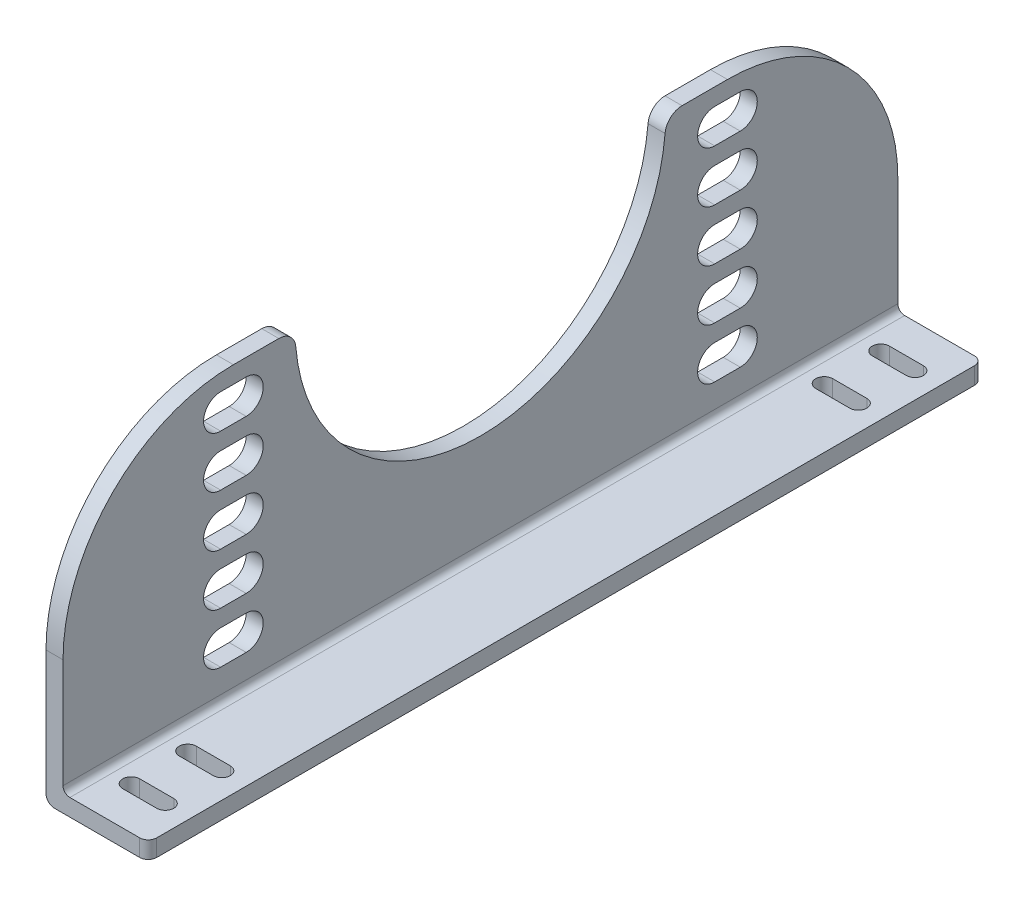
SolidWorks part; units mm, degrees
material "PA9"
ref_plane "Płaszczyzna przednia" through (0, 0, 0) normal (0, 0, 1) x (1, 0, 0)
ref_plane "Płaszczyzna górna" through (0, 0, 0) normal (0, 1, 0) x (1, 0, 0)
ref_plane "Płaszczyzna prawa" through (0, 0, 0) normal (1, 0, 0) x (0, 0, -1)
sketch "Szkic1" plane through (0, 0, 0) normal (0, 0, 1) x (1, 0, 0)
  line L1 (0, 0) -> (-10, 0)
  line L2 (0, 0) -> (0, 178)
  line L3 (0, 178) -> (-10, 178)
  line L4 (-10, 0) -> (-10, 178)
  dimension "D1" = 10
  dimension "D2" = 178
extrude "Dodanie-wyciągnięcie1" add sketch "Szkic1" along normal blind 490
sketch "Szkic2" plane through (0, 0, 0) normal (1, 0, 0) x (0, 0, -1)
  line L0 (-107.5, 158) -> (-92.5, 158) construction
  line L1 (-107.5, 168) -> (-92.5, 168)
  line L2 (-107.5, 148) -> (-92.5, 148)
  line L3 (-490, 178) -> (0, 178) construction
  line L5 (-107.5, 128) -> (-92.5, 128) construction
  line L6 (-107.5, 138) -> (-92.5, 138)
  line L7 (-107.5, 118) -> (-92.5, 118)
  line L8 (-107.5, 98) -> (-92.5, 98) construction
  line L9 (-107.5, 108) -> (-92.5, 108)
  line L10 (-107.5, 88) -> (-92.5, 88)
  line L11 (-107.5, 68) -> (-92.5, 68) construction
  line L12 (-107.5, 78) -> (-92.5, 78)
  line L13 (-107.5, 58) -> (-92.5, 58)
  line L14 (-107.5, 38) -> (-92.5, 38) construction
  line L15 (-107.5, 48) -> (-92.5, 48)
  line L16 (-107.5, 28) -> (-92.5, 28)
  line L17 (0, 0) -> (0, 178) construction
  arc A0 (-107.5, 168) -> (-107.5, 148) centre (-107.5, 158) ccw
  arc A1 (-92.5, 148) -> (-92.5, 168) centre (-92.5, 158) ccw
  arc A2 (-107.5, 138) -> (-107.5, 118) centre (-107.5, 128) ccw
  arc A3 (-92.5, 118) -> (-92.5, 138) centre (-92.5, 128) ccw
  arc A4 (-107.5, 108) -> (-107.5, 88) centre (-107.5, 98) ccw
  arc A5 (-92.5, 88) -> (-92.5, 108) centre (-92.5, 98) ccw
  arc A6 (-107.5, 78) -> (-107.5, 58) centre (-107.5, 68) ccw
  arc A7 (-92.5, 58) -> (-92.5, 78) centre (-92.5, 68) ccw
  arc A8 (-107.5, 48) -> (-107.5, 28) centre (-107.5, 38) ccw
  arc A9 (-92.5, 28) -> (-92.5, 48) centre (-92.5, 38) ccw
  point P2 (-100, 158)
  point P15 (-100, 128)
  point P22 (-100, 98)
  point P29 (-100, 68)
  point P36 (-100, 38)
  dimension "D1" = 10
  dimension "D2" = 15
  dimension "D3" = 20
  dimension "D4" = 100
  dimension "D5" = 5
extrude "Wytnij-wyciągnięcie1" cut sketch "Szkic2" against normal through all
sketch "Szkic3" plane through (0, 0, 0) normal (1, 0, 0) x (0, 0, -1)
  line L0 (-397.5, 158) -> (-382.5, 158) construction
  line L1 (-397.5, 168) -> (-382.5, 168)
  line L2 (-397.5, 148) -> (-382.5, 148)
  line L3 (-490, 178) -> (0, 178) construction
  line L4 (-92.5, 168) -> (-107.5, 168) construction
  line L5 (-397.5, 128) -> (-382.5, 128) construction
  line L6 (-397.5, 138) -> (-382.5, 138)
  line L7 (-397.5, 118) -> (-382.5, 118)
  line L8 (-397.5, 98) -> (-382.5, 98) construction
  line L9 (-397.5, 108) -> (-382.5, 108)
  line L10 (-397.5, 88) -> (-382.5, 88)
  line L11 (-397.5, 68) -> (-382.5, 68) construction
  line L12 (-397.5, 78) -> (-382.5, 78)
  line L13 (-397.5, 58) -> (-382.5, 58)
  line L14 (-397.5, 38) -> (-382.5, 38) construction
  line L15 (-397.5, 48) -> (-382.5, 48)
  line L16 (-397.5, 28) -> (-382.5, 28)
  arc A0 (-397.5, 168) -> (-397.5, 148) centre (-397.5, 158) ccw
  arc A1 (-382.5, 148) -> (-382.5, 168) centre (-382.5, 158) ccw
  arc A2 (-397.5, 138) -> (-397.5, 118) centre (-397.5, 128) ccw
  arc A3 (-382.5, 118) -> (-382.5, 138) centre (-382.5, 128) ccw
  arc A4 (-397.5, 108) -> (-397.5, 88) centre (-397.5, 98) ccw
  arc A5 (-382.5, 88) -> (-382.5, 108) centre (-382.5, 98) ccw
  arc A6 (-397.5, 78) -> (-397.5, 58) centre (-397.5, 68) ccw
  arc A7 (-382.5, 58) -> (-382.5, 78) centre (-382.5, 68) ccw
  arc A8 (-397.5, 48) -> (-397.5, 28) centre (-397.5, 38) ccw
  arc A9 (-382.5, 28) -> (-382.5, 48) centre (-382.5, 38) ccw
  point P2 (-390, 158)
  point P11 (-100, 168)
  point P15 (-390, 128)
  point P22 (-390, 98)
  point P29 (-390, 68)
  point P36 (-390, 38)
  dimension "D1" = 10
  dimension "D2" = 15
  dimension "D3" = 20
  dimension "D4" = 290
  dimension "D5" = 5
extrude "Wytnij-wyciągnięcie2" cut sketch "Szkic3" against normal through all
fillet "Zaokrąglenie1" radius 100 1 edges at (-5, 178, 0)
fillet "Zaokrąglenie2" radius 100 1 edges at (-5, 178, 490)
sketch "Szkic5" plane through (-10, 0, 0) normal (-1, 0, 0) x (0, 0, 1)
  line L0 (390, 178) -> (100, 178) construction
  line L1 (136.2352, 178) -> (353.7648, 178)
  arc A0 (136.2352, 178) -> (353.7648, 178) centre (245, 178) ccw
extrude "Wytnij-wyciągnięcie3" cut sketch "Szkic5" against normal through all
fillet "Zaokrąglenie3" radius 10 2 edges at (-5, 178, 353.7648) (-5, 178, 136.2352)
sketch "Szkic6" plane through (0, 0, 0) normal (0, 0, -1) x (-1, 0, 0)
  line L1 (10, 0) -> (-50, 0)
  line L2 (10, 0) -> (10, 10)
  line L3 (10, 10) -> (-50, 10)
  line L4 (-50, 0) -> (-50, 10)
  dimension "D1" = 60
  dimension "D2" = 10
extrude "Dodanie-wyciągnięcie2" add sketch "Szkic6" against normal through all
fillet "Zaokrąglenie4" radius 5 1 edges at (-10, 0, 245)
fillet "Zaokrąglenie5" radius 4 1 edges at (0, 10, 245)
fillet "Zaokrąglenie6" radius 5 2 edges at (50, 5, 0) (50, 5, 490)
sketch "Szkic7" plane through (0, 10, 0) normal (0, 1, 0) x (1, 0, 0)
  line L0 (35, -465) -> (15, -465) construction
  line L1 (35, -470) -> (15, -470)
  line L2 (35, -460) -> (15, -460)
  line L3 (4, -490) -> (45, -490) construction
  line L4 (50, -485) -> (50, -5) construction
  arc A0 (35, -470) -> (35, -460) centre (35, -465) ccw
  arc A1 (15, -460) -> (15, -470) centre (15, -465) ccw
  point P2 (25, -465)
  dimension "D2" = 5
  dimension "D1" = 20
  dimension "D3" = 25
  dimension "D4" = 25
extrude "Wytnij-wyciągnięcie4" cut sketch "Szkic7" against normal blind 10
ref_plane "Płaszczyzna1" through (0, 0, 245) normal (0, 0, -1) x (-1, 0, 0)
mirror "Lustro2" about plane through (0, 0, 245) normal (0, 0, -1) of "Wytnij-wyciągnięcie4"
sketch "Szkic8" plane through (0, 10, 0) normal (0, 1, 0) x (1, 0, 0)
  line L3 (50, -485) -> (50, -5) construction
  line L5 (15, -431.8) -> (35, -431.8) construction
  line L6 (15, -426.8) -> (35, -426.8)
  line L7 (15, -436.8) -> (35, -436.8)
  line L8 (4, -490) -> (45, -490) construction
  arc A2 (15, -426.8) -> (15, -436.8) centre (15, -431.8) ccw
  arc A3 (35, -436.8) -> (35, -426.8) centre (35, -431.8) ccw
  point P13 (25, -431.8)
  dimension "D7" = 5
  dimension "D5" = 58.2
  dimension "D6" = 20
  dimension "D8" = 25
extrude "Wytnij-wyciągnięcie5" cut sketch "Szkic8" against normal blind 10
mirror "Lustro3" about plane through (0, 0, 245) normal (0, 0, -1) of "Wytnij-wyciągnięcie5"
sketch "Szkic9" plane through (0, 10, 0) normal (0, 1, 0) x (1, 0, 0)
  line L0 (35, -426.8) -> (15, -426.8) construction
  circle A0 centre (25, -435) radius 15.9474
  dimension "D1" = 8.2
